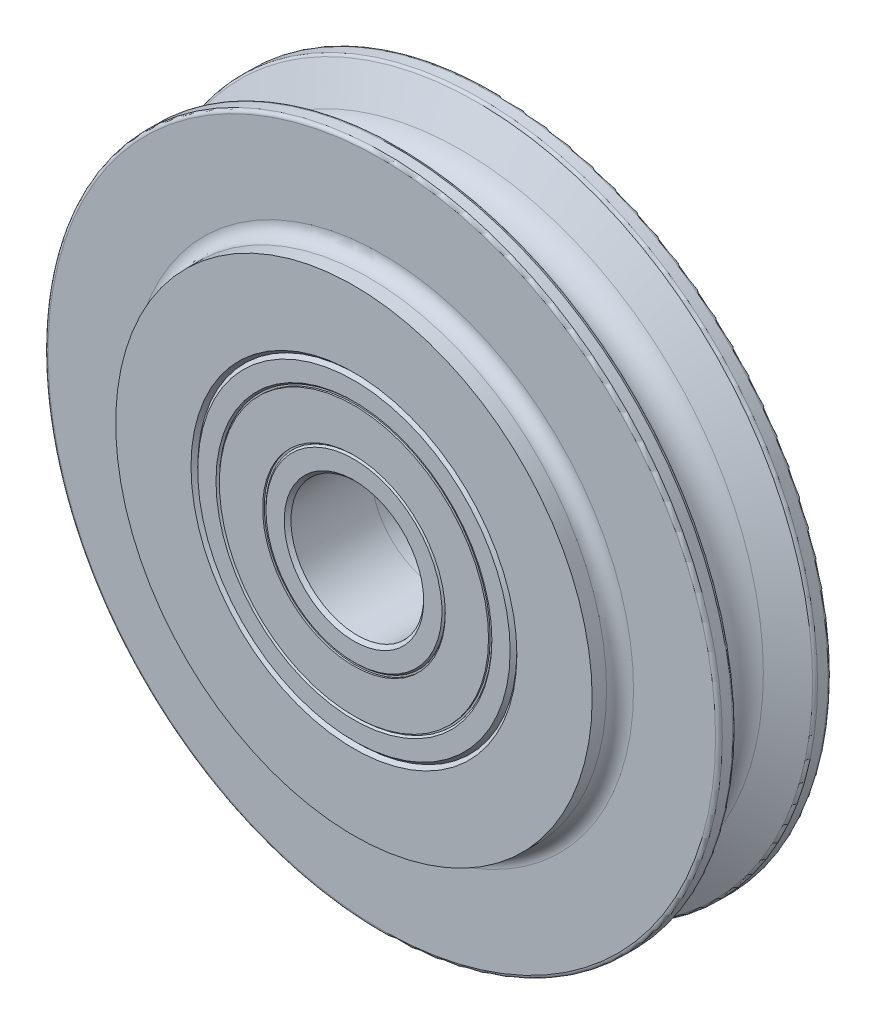
SolidWorks part; units mm, degrees
ref_plane "Front Plane" through (0, 0, 0) normal (0, 0, 1) x (1, 0, 0)
ref_plane "Top Plane" through (0, 0, 0) normal (0, 1, 0) x (1, 0, 0)
ref_plane "Right Plane" through (0, 0, 0) normal (1, 0, 0) x (0, 0, -1)
sketch "Sketch1" plane through (0, 0, 0) normal (0, 0, 1) x (1, 0, 0)
  line L0 (0, 0) -> (0, 76.2) construction
  circle A0 centre (0, 0) radius 76.2
  circle A1 centre (0, 0) radius 15
  circle A2 centre (0, 0) radius 64.9986
  point P5 (0, 76.2)
  point P6 (0, 64.9986)
  point P7 (0, 15)
  dimension "OD" = 152.4
  dimension "For Shaft Diameter" = 30
  dimension "Pulley Diameter" = 129.9972
sketch "Sketch2" plane through (0, 0, 0) normal (1, 0, 0) x (0, 0, -1)
  line L0 (-18.9992, 0) -> (18.9992, 0) construction
  line L1 (-18.9992, 0) -> (-18.9992, 15)
  line L2 (-18.9992, 15) -> (18.9992, 15) construction
  line L3 (18.9992, 15) -> (18.9992, 0)
  line L4 (-18.9992, 15) -> (-18.9992, 36.068)
  line L5 (-18.9992, 36.068) -> (18.9992, 36.068)
  line L6 (18.9992, 36.068) -> (18.9992, 15)
  line L7 (-18.9992, 36.068) -> (-18.9992, 53.848)
  line L8 (-18.9992, 53.848) -> (-12.7, 53.848)
  line L9 (-12.7, 53.848) -> (-12.7, 76.2)
  line L10 (-12.7, 76.2) -> (0, 76.2)
  line L11 (0, 76.2) -> (0, 0) construction
  line L12 (-18.9992, 35.306) -> (-18.2372, 36.068)
  line L13 (-5.2508, 68.2796) -> (-8.905, 75.772)
  arc A0 (0, 64.9986) -> (-5.2508, 68.2796) centre (0, 70.8406) cw
  arc A1 (-8.905, 75.772) -> (-9.5899, 76.2) centre (-9.5899, 75.438) ccw
  circle A2 centre (0, 69.7611) radius 4.7625 construction
  arc A3 (-15.748, 53.848) -> (-12.7, 56.896) centre (-15.748, 56.896) ccw
  arc A4 (-12.7, 75.438) -> (-11.938, 76.2) centre (-11.938, 75.438) cw
  circle A5 centre (0, -69.7611) radius 4.7625 construction
  point P31 (0, -64.9986)
  point P32 (0, 64.9986)
  dimension "D8" = 0.762
  dimension "D9" = 5.842
  dimension "For Rope Diameter" = 9.525
  dimension "D11" = 3.048
  dimension "D12" = 0.762
  dimension "Width" = 37.9984
  dimension "D2" = 36.068
  dimension "D3" = 25.4
  dimension "D4" = 53.848
  dimension "D5" = 45
  dimension "D6" = 0.762
  dimension "D7" = 26
sketch "Sketch3" plane through (0, 0, 0) normal (1, 0, 0) x (0, 0, -1)
  line L0 (-18.9992, 15) -> (-18.9992, 20.267) construction
  line L1 (-18.9992, 15) -> (-18.9992, 36.068) construction
  line L2 (-18.9992, 36.068) -> (-18.9992, 30.801) construction
  line L4 (-18.9992, 30.801) -> (-17.4752, 30.801)
  line L5 (-18.9992, 30.801) -> (-18.9992, 20.267)
  line L6 (-18.9992, 20.267) -> (-17.4752, 20.267)
  line L7 (-17.4752, 30.801) -> (-17.4752, 20.267)
  dimension "D1" = 1.524
  dimension "D2" = 10.534
sketch "Sketch4" plane through (0, 0, 0) normal (1, 0, 0) x (0, 0, -1)
  line L0 (-18.9992, 15) -> (0, 15)
  line L1 (0, 15) -> (0, 36.068)
  line L2 (0, 64.9986) -> (0, -64.9986) construction
  line L3 (0, 36.068) -> (-18.2372, 36.068)
  line L4 (-18.2372, 36.068) -> (-18.9992, 35.306)
  line L5 (-18.9992, 35.306) -> (-18.9992, 30.801)
  line L6 (-18.9992, 30.801) -> (-17.4752, 30.801)
  line L7 (-17.4752, 30.801) -> (-17.4752, 20.267)
  line L8 (-17.4752, 20.267) -> (-18.9992, 20.267)
  line L9 (-18.9992, 20.267) -> (-18.9992, 15)
  line L10 (-18.9992, 0) -> (18.9992, 0) construction
  line L11 (-18.9992, 0) -> (18.9992, 0) construction
revolve "Revolve1" add sketch "Sketch4" angle 360 about L11
chamfer "Chamfer1" distance 0.381 angle 45 2 edges at (30.801, 0, 18.9992) (20.267, 0, 18.9992)
sketch "Sketch5" plane through (0, 0, 0) normal (1, 0, 0) x (0, 0, -1)
  line L0 (-18.9992, 30.801) -> (-18.9992, 20.267) construction
  line L1 (-18.9992, 20.267) -> (-17.4752, 20.267) construction
  line L2 (-17.4752, 30.801) -> (-17.4752, 20.267) construction
  line L3 (-18.9992, 30.801) -> (-17.4752, 30.801) construction
  line L4 (-18.9992, 30.801) -> (-18.9992, 20.267)
  line L5 (-18.9992, 20.267) -> (-17.4752, 20.267)
  line L6 (-17.4752, 30.801) -> (-17.4752, 20.267)
  line L7 (-18.9992, 30.801) -> (-17.4752, 30.801)
  line L8 (-18.9992, 0) -> (18.9992, 0) construction
  line L9 (-18.9992, 0) -> (18.9992, 0) construction
revolve "Revolve2" add sketch "Sketch5" angle 360 about L9
sketch "Sketch7" plane through (0, 0, 18.9992) normal (0, 0, 1) x (1, 0, 0)
  circle A0 centre (0, 0) radius 30.801 construction
  circle A1 centre (0, 0) radius 30.801
  circle A2 centre (0, 0) radius 30.42
  circle A3 centre (0, 0) radius 20.267 construction
  circle A4 centre (0, 0) radius 20.267
  circle A5 centre (0, 0) radius 20.648
  circle M1 centre (0, 0) radius 20.267
  circle M2 centre (0, 0) radius 30.801
  dimension "D1" = 0.381
  dimension "D2" = 0.381
extrude "Cut-Extrude1" cut sketch "Sketch7" against normal blind 0.381 contours A5 M1 | A2 M2
chamfer "Chamfer4" distance 0.762 angle 45 1 edges at (15, 0, 18.9992)
mirror "Mirror1" about plane through (0, 0, 0) normal (0, 0, 1) of bodies 110 104 105
sketch "Sketch6" plane through (0, 0, 0) normal (1, 0, 0) x (0, 0, -1)
  line L0 (-18.2372, 36.068) -> (-18.9992, 36.83)
  line L1 (-18.9992, 36.068) -> (-18.9992, 53.848) construction
  line L2 (-18.9992, 35.306) -> (-18.2372, 36.068) construction
  line L3 (-18.9992, 36.83) -> (-18.9992, 53.848)
  line L4 (-18.9992, 53.848) -> (-15.748, 53.848)
  line L5 (-12.7, 56.896) -> (-12.7, 75.438)
  line L6 (-5.2508, 68.2796) -> (-8.905, 75.772) construction
  line L7 (-5.2508, 68.2796) -> (-8.905, 75.772)
  line L8 (-11.938, 76.2) -> (-9.5899, 76.2)
  line L9 (0, 64.9986) -> (0, 36.068)
  line L10 (0, 64.9986) -> (0, -64.9986) construction
  line L11 (0, 36.068) -> (-18.2372, 36.068)
  line L12 (-18.9992, 0) -> (18.9992, 0) construction
  line L13 (-18.9992, 0) -> (18.9992, 0) construction
  arc A0 (-15.748, 53.848) -> (-12.7, 56.896) centre (-15.748, 56.896) ccw construction
  arc A1 (-15.748, 53.848) -> (-12.7, 56.896) centre (-15.748, 56.896) ccw
  arc A2 (-5.2508, 68.2796) -> (0, 64.9986) centre (0, 70.8406) ccw construction
  arc A3 (-8.905, 75.772) -> (-9.5899, 76.2) centre (-9.5899, 75.438) ccw construction
  arc A4 (-11.938, 76.2) -> (-12.7, 75.438) centre (-11.938, 75.438) ccw construction
  arc A5 (-5.2508, 68.2796) -> (0, 64.9986) centre (0, 70.8406) ccw
  arc A6 (-8.905, 75.772) -> (-9.5899, 76.2) centre (-9.5899, 75.438) ccw
  arc A7 (-11.938, 76.2) -> (-12.7, 75.438) centre (-11.938, 75.438) ccw
revolve "Revolve3" add sketch "Sketch6" angle 360 about L13
mirror "Mirror2" about plane through (0, 64.9986, 0) normal (0, 0, 1) of bodies 108
equation "\"D1@Sketch3\"=2*\"D6@Sketch2\""
equation "\"D2@Sketch3\"=(\"D2@Sketch2\"-(0.5*\"For Shaft Diameter@Sketch1\"))/2"
equation "\"D1@Chamfer1\"=0.5*\"D6@Sketch2\""
equation "\"D1@Chamfer4\"=\"D6@Sketch2\""
equation "\"D1@Sketch7\"=\"D6@Sketch2\"*0.5"
equation "\"D1@Cut-Extrude1\"=\"D1@Chamfer1\""
equation "\"D2@Sketch7\"=\"D1@Sketch7\""
